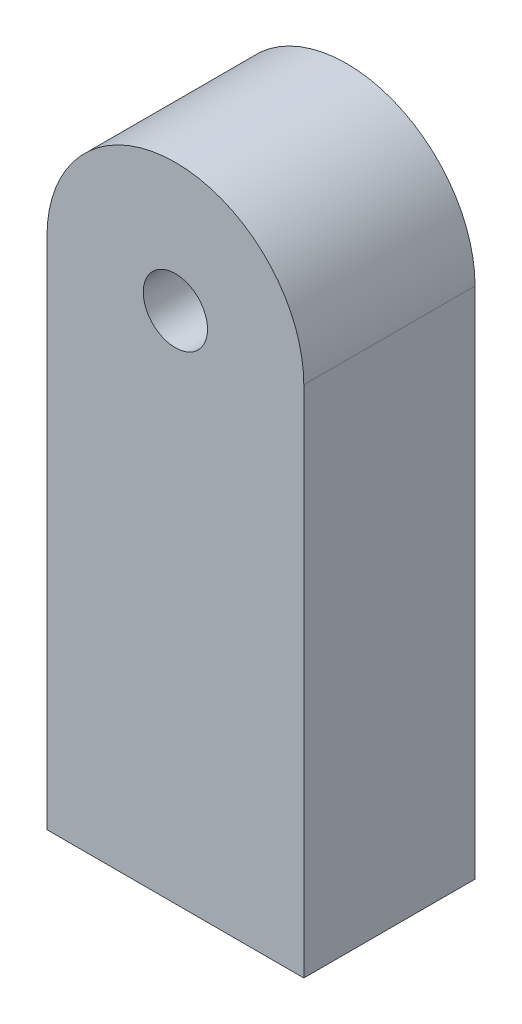
SolidWorks part; units mm, degrees
ref_plane "Front Plane" through (0, 0, 0) normal (0, 0, 1) x (1, 0, 0)
ref_plane "Top Plane" through (0, 0, 0) normal (0, 1, 0) x (1, 0, 0)
ref_plane "Right Plane" through (0, 0, 0) normal (1, 0, 0) x (0, 0, -1)
sketch "Sketch2" plane through (0, 0, 0) normal (0, 1, 0) x (1, 0, 0)
  line L1 (-19.05, -12.7) -> (19.05, -12.7)
  line L2 (-19.05, -12.7) -> (-19.05, 12.7)
  line L3 (-19.05, 12.7) -> (19.05, 12.7)
  line L4 (19.05, -12.7) -> (19.05, 12.7)
  line L5 (-19.05, -12.7) -> (19.05, 12.7) construction
  line L6 (-19.05, 12.7) -> (19.05, -12.7) construction
  point P0 (0, 0)
  dimension "D1" = 25.4
  dimension "D2" = 38.1
extrude "Boss-Extrude1" add sketch "Sketch2" along normal blind 76.2
sketch "Sketch3" plane through (0, 76.2, 0) normal (0, 1, 0) x (1, 0, 0)
  line L0 (19.05, 12.7) -> (-19.05, 12.7) construction
  line L1 (0, 12.7) -> (19.05, 12.7)
  line L2 (0, 12.7) -> (0, -12.7)
  line L3 (0, -12.7) -> (19.05, -12.7)
  line L4 (19.05, 12.7) -> (19.05, -12.7)
  line L5 (0, 12.7) -> (19.05, -12.7) construction
  line L6 (0, -12.7) -> (19.05, 12.7) construction
  point P4 (9.525, 0)
revolve "Revolve1" add sketch "Sketch3" angle 180 about L2
sketch "Sketch4" plane through (0, 0, 12.7) normal (0, 0, 1) x (1, 0, 0)
  line L0 (0, 0) -> (0, 76.2) construction
  line L1 (-19.05, 0) -> (19.05, 0) construction
  circle A0 centre (0, 76.2) radius 4.7625
  dimension "D2" = 9.525
  dimension "D1" = 76.2
extrude "Cut-Extrude1" cut sketch "Sketch4" against normal through all
